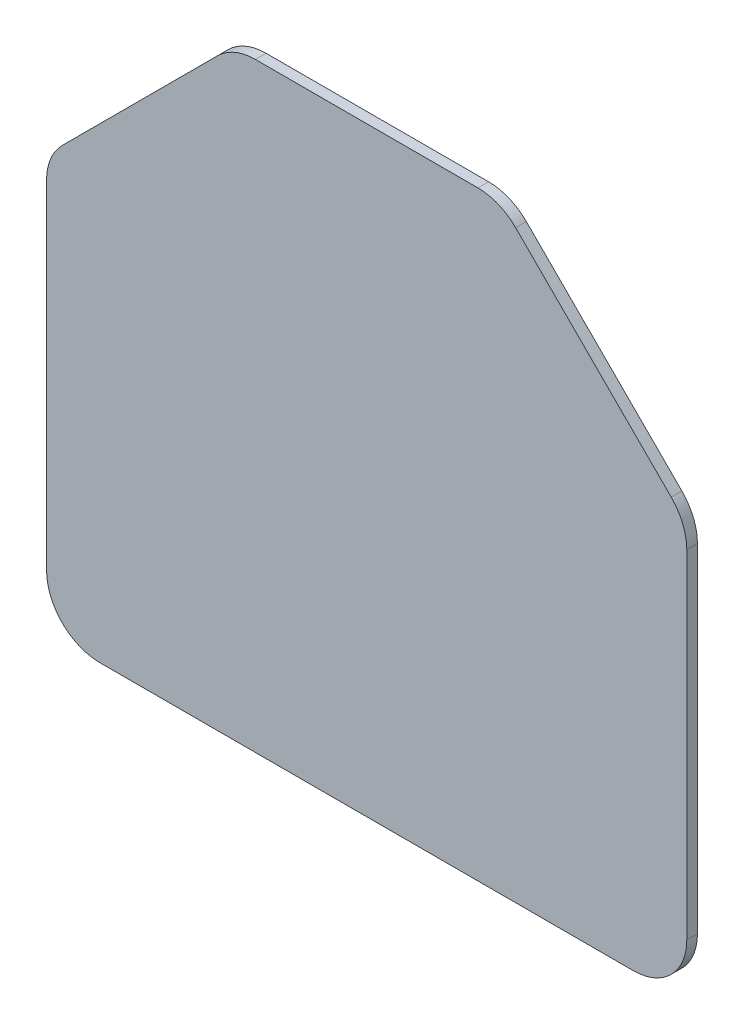
SolidWorks part; units mm, degrees
ref_plane "前视基准面" through (0, 0, 0) normal (0, 0, 1) x (1, 0, 0)
ref_plane "上视基准面" through (0, 0, 0) normal (0, 1, 0) x (1, 0, 0)
ref_plane "右视基准面" through (0, 0, 0) normal (1, 0, 0) x (0, 0, -1)
sketch "草图3" plane through (0, 0, 0) normal (0, 0, 1) x (1, 0, 0)
  line L1 (73.5057, 259.0895) -> (156.9372, 259.0895)
  line L2 (-4.7785, 180.8052) -> (-4.7785, 54.0895)
  line L3 (15.2215, 34.0895) -> (215.2215, 34.0895)
  line L4 (235.2215, 180.8052) -> (235.2215, 54.0895)
  line L6 (1.0793, 194.9474) -> (59.3636, 253.2316)
  line L9 (171.0793, 253.2316) -> (229.3636, 194.9474)
  arc A0 (73.5057, 259.0895) -> (59.3636, 253.2316) centre (73.5057, 239.0895) ccw
  arc A1 (171.0793, 253.2316) -> (156.9372, 259.0895) centre (156.9372, 239.0895) ccw
  arc A2 (1.0793, 194.9474) -> (-4.7785, 180.8052) centre (15.2215, 180.8052) ccw
  arc A3 (-4.7785, 54.0895) -> (15.2215, 34.0895) centre (15.2215, 54.0895) ccw
  arc A4 (215.2215, 34.0895) -> (235.2215, 54.0895) centre (215.2215, 54.0895) ccw
  arc A5 (235.2215, 180.8052) -> (229.3636, 194.9474) centre (215.2215, 180.8052) ccw
  dimension "D1" = 20
  dimension "D2" = 20
  dimension "D3" = 20
extrude "凸台-拉伸1" add sketch "草图3" along normal blind 4
